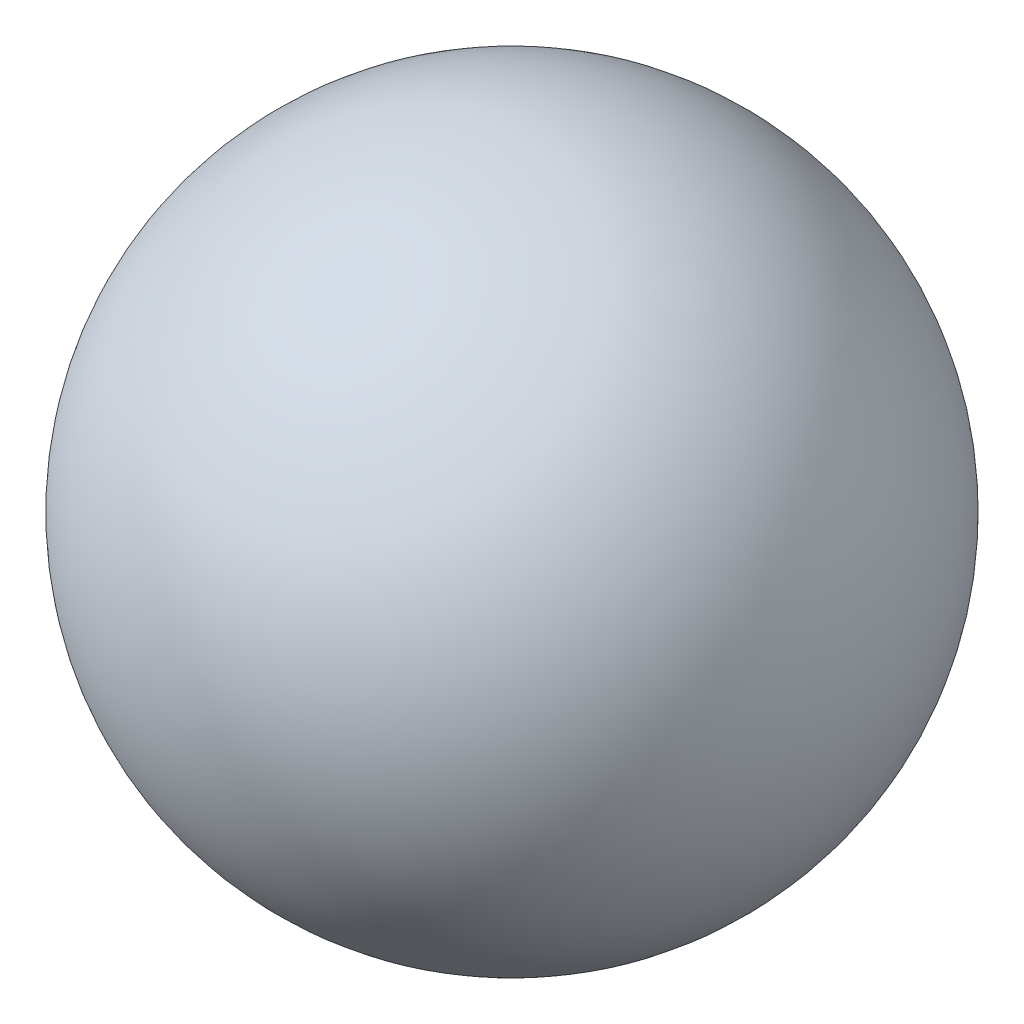
SolidWorks part; units mm, degrees
ref_plane "前视基准面" through (0, 0, 0) normal (0, 0, 1) x (1, 0, 0)
ref_plane "上视基准面" through (0, 0, 0) normal (0, 1, 0) x (1, 0, 0)
ref_plane "右视基准面" through (0, 0, 0) normal (1, 0, 0) x (0, 0, -1)
sketch "草图1" plane through (0, 0, 0) normal (1, 0, 0) x (0, 0, -1)
  line L0 (0, 8.5) -> (0, -8.5)
  arc A0 (0, -8.5) -> (0, 8.5) centre (0, 0) ccw
  dimension "D1" = 17
revolve "旋转1" add sketch "草图1" angle 360 about L0
